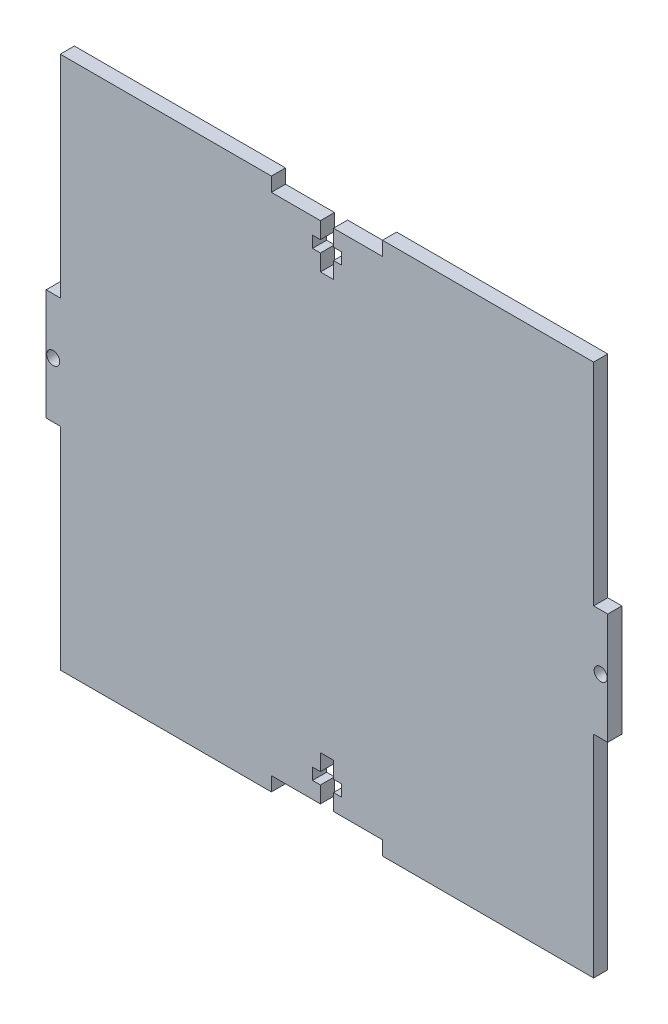
SolidWorks part; units mm, degrees
ref_plane "Front Plane" through (0, 0, 0) normal (0, 0, 1) x (1, 0, 0)
ref_plane "Top Plane" through (0, 0, 0) normal (0, 1, 0) x (1, 0, 0)
ref_plane "Right Plane" through (0, 0, 0) normal (1, 0, 0) x (0, 0, -1)
sketch "Sketch1" plane through (0, 0, 0) normal (0, 0, 1) x (1, 0, 0)
  line L0 (0, 60) -> (0, -60) construction
  line L1 (-60, 60) -> (60, 60)
  line L2 (-60, 60) -> (-60, -60)
  line L3 (-60, -60) -> (60, -60)
  line L4 (60, 60) -> (60, -60)
  line L5 (-60, 60) -> (60, -60) construction
  line L6 (-60, -60) -> (60, 60) construction
  line L7 (-60, 0) -> (60, 0) construction
  line L8 (-3.25, -50.525) -> (3.25, -50.525)
  line L9 (12.5, 60) -> (-12.5, 60)
  line L10 (12.5, 60) -> (12.5, 56.825)
  line L11 (12.5, 56.825) -> (-12.5, 56.825)
  line L12 (-12.5, 60) -> (-12.5, 56.825)
  line L13 (12.5, 60) -> (-12.5, 56.825) construction
  line L14 (12.5, 56.825) -> (-12.5, 60) construction
  line L15 (-1.47, 56.825) -> (1.47, 56.825)
  line L16 (-1.47, 56.825) -> (-1.47, 46.825)
  line L17 (-1.47, 46.825) -> (1.47, 46.825)
  line L18 (1.47, 56.825) -> (1.47, 46.825)
  line L19 (-1.47, 56.825) -> (1.47, 46.825) construction
  line L20 (-1.47, 46.825) -> (1.47, 56.825) construction
  line L21 (-3.25, 53.125) -> (3.25, 53.125)
  line L22 (-3.25, 53.125) -> (-3.25, 50.525)
  line L23 (-3.25, 50.525) -> (3.25, 50.525)
  line L24 (3.25, 53.125) -> (3.25, 50.525)
  line L25 (-3.25, 53.125) -> (3.25, 50.525) construction
  line L26 (-3.25, 50.525) -> (3.25, 53.125) construction
  line L27 (3.25, -53.125) -> (3.25, -50.525)
  line L28 (-3.25, -53.125) -> (3.25, -53.125)
  line L29 (-3.25, -53.125) -> (-3.25, -50.525)
  line L30 (-1.47, -46.825) -> (1.47, -46.825)
  line L31 (1.47, -56.825) -> (1.47, -46.825)
  line L32 (-1.47, -56.825) -> (1.47, -56.825)
  line L33 (-1.47, -56.825) -> (-1.47, -46.825)
  line L34 (12.5, -56.825) -> (-12.5, -56.825)
  line L35 (-12.5, -60) -> (-12.5, -56.825)
  line L36 (12.5, -60) -> (-12.5, -60)
  line L37 (12.5, -60) -> (12.5, -56.825)
  line L38 (63.175, -12.5) -> (60, -12.5)
  line L39 (-63.175, 12.5) -> (-60, 12.5)
  line L40 (-63.175, 12.5) -> (-63.175, -12.5)
  line L41 (-63.175, -12.5) -> (-60, -12.5)
  line L42 (-60, 12.5) -> (-60, -12.5)
  line L43 (-63.175, 12.5) -> (-60, -12.5) construction
  line L44 (-63.175, -12.5) -> (-60, 12.5) construction
  line L45 (60, 12.5) -> (60, -12.5)
  line L46 (63.175, 12.5) -> (60, 12.5)
  line L47 (63.175, 12.5) -> (63.175, -12.5)
  circle A0 centre (-61.5875, 0) radius 1.47
  circle A1 centre (61.5875, 0) radius 1.47
  point P0 (0, 0)
  point P10 (0, 58.4125)
  point P15 (0, 51.825)
  point P20 (0, 51.825)
  point P37 (-61.5875, 0)
  dimension "D11" = 2.94
  dimension "D1" = 120
  dimension "D2" = 120
  dimension "D3" = 3.175
  dimension "D4" = 10
  dimension "D5" = 2.94
  dimension "D6" = 25
  dimension "D7" = 6.5
  dimension "D8" = 2.6
  dimension "D9" = 6.3
  dimension "D10" = 3.175
extrude "Boss-Extrude1" add sketch "Sketch1" along normal mid plane 3.175 contours L21 L24 L23 L18 L17 L16 L22 L11 L12 L1 L2 L3 L4 L10 | L40 L39 L42 L41 | A0 | L38 L45 L46 L47 | A1
